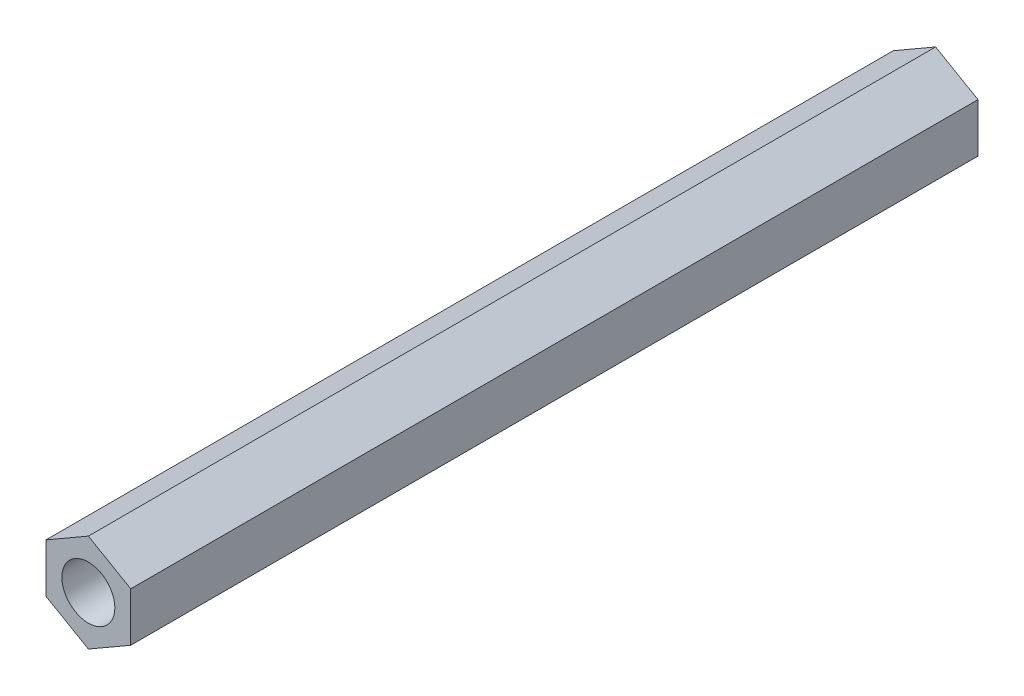
SolidWorks part; units mm, degrees
material "2.0402 (CuZn40Pb2)"
ref_plane "前视基准面" through (0, 0, 0) normal (0, 0, 1) x (1, 0, 0)
ref_plane "上视基准面" through (0, 0, 0) normal (0, 1, 0) x (1, 0, 0)
ref_plane "右视基准面" through (0, 0, 0) normal (1, 0, 0) x (0, 0, -1)
other "Configuration Table"
sketch "草图1" plane through (0, 0, 0) normal (0, 0, 1) x (1, 0, 0)
  line L1 (4, -2.3094) -> (4, 2.3094)
  line L2 (4, 2.3094) -> (0, 4.6188)
  line L3 (0, 4.6188) -> (-4, 2.3094)
  line L4 (-4, 2.3094) -> (-4, -2.3094)
  line L5 (-4, -2.3094) -> (0, -4.6188)
  line L6 (0, -4.6188) -> (4, -2.3094)
  circle A0 centre (0, 0) radius 4 construction
  dimension "D1" = 8
extrude "凸台-拉伸1" add sketch "草图1" along normal blind 80
sketch "草图2" plane through (0, 0, 80) normal (0, 0, 1) x (1, 0, 0)
  circle A0 centre (0, 0) radius 2.5
  dimension "D1" = 5
extrude "切除-拉伸1" cut sketch "草图2" against normal through all
cosmetic thread "装饰螺纹线1" parameters "D2"=6
